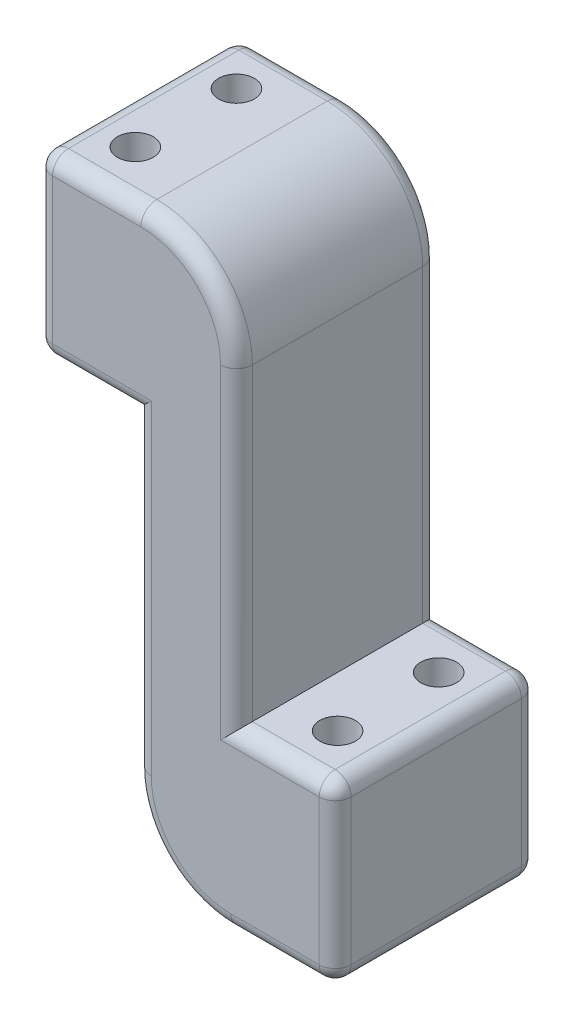
SolidWorks part; units mm, degrees
ref_plane "Front Plane" through (0, 0, 0) normal (0, 0, 1) x (1, 0, 0)
ref_plane "Top Plane" through (0, 0, 0) normal (0, 1, 0) x (1, 0, 0)
ref_plane "Right Plane" through (0, 0, 0) normal (1, 0, 0) x (0, 0, -1)
sketch "Sketch1" plane through (0, 0, 0) normal (0, 0, 1) x (1, 0, 0)
  line L0 (0, -23.8252) -> (-45.3315, -23.8252) construction
  line L1 (-2, 0) -> (-12.3952, 0)
  line L2 (0, -2) -> (0, -20.2504)
  line L3 (-2, -22.2504) -> (-12.3952, -22.2504)
  line L4 (-12.3952, 0) -> (-12.3952, -22.2504)
  line L5 (-25.0952, 28.5496) -> (-35.4904, 28.5496)
  line L6 (-25.0952, 28.5496) -> (-25.0952, 50.8)
  line L7 (-25.0952, 50.8) -> (-35.4904, 50.8)
  line L8 (-37.4904, 30.5496) -> (-37.4904, 48.8)
  line L9 (-25.0952, 50.8) -> (-24.3952, 50.8)
  line L10 (-12.3952, 38.8) -> (-12.3952, 0)
  line L11 (-12.3952, -22.2504) -> (-13.0952, -22.2504)
  line L12 (-25.0952, -10.2504) -> (-25.0952, 28.5496)
  line L13 (-48.1495, 26.9748) -> (9.176, 26.9748) construction
  arc A0 (-13.0952, -22.2504) -> (-25.0952, -10.2504) centre (-13.0952, -10.2504) cw
  arc A1 (-12.3952, 38.8) -> (-24.3952, 50.8) centre (-24.3952, 38.8) ccw
  arc A2 (0, -2) -> (-2, 0) centre (-2, -2) ccw
  arc A3 (0, -20.2504) -> (-2, -22.2504) centre (-2, -20.2504) cw
  arc A4 (-35.4904, 28.5496) -> (-37.4904, 30.5496) centre (-35.4904, 30.5496) cw
  arc A5 (-37.4904, 48.8) -> (-35.4904, 50.8) centre (-35.4904, 48.8) cw
  point P19 (0, 0)
  point P22 (0, -22.2504)
  point P29 (-30.2928, 28.5496)
  dimension "D6" = 12
  dimension "D7" = 2
  dimension "D1" = 22.2504
  dimension "D2" = 12.3952
  dimension "D3" = 12.7
  dimension "D4" = 1.5748
  dimension "D5" = 1.5748
  dimension "D8" = 50.8
extrude "Boss-Extrude1" add sketch "Sketch1" along normal blind 25.4 contours L10 A1 L9 L6 L12 A0 L11 L4 | A5 L8 A4 L5 L6 L7 | A3 L2 A2 L1 L4 L3
sketch "Sketch2" plane through (0, 50.8, 0) normal (0, 1, 0) x (1, 0, 0)
  line L0 (-35.4904, 0) -> (-24.3952, 0) construction
  line L1 (-37.4904, -25.4) -> (-37.4904, 0) construction
  line L2 (-35.4904, -25.4) -> (-24.3952, -25.4) construction
  line L3 (0, -25.4) -> (0, 0) construction
  circle A0 centre (-31.4452, -6.35) radius 2.25
  circle A1 centre (-31.4452, -19.05) radius 2.25
  circle A2 centre (-6.0452, -6.35) radius 2.25
  circle A3 centre (-6.0452, -19.05) radius 2.25
  dimension "D1" = 4.5
  dimension "D2" = 6.35
  dimension "D4" = 6.0452
  dimension "D5" = 6.35
  dimension "D6" = 6.0452
extrude "Cut-Extrude1" cut sketch "Sketch2" against normal through all
fillet "Fillet1" radius 2 28 edges at (-7.1976, 0, 0) (-0.5858, -0.5858, 0) (0, -11.1252, 0) (-0.5858, -21.6646, 0) (-7.5476, -22.2504, 0) (-21.5805, -18.7357, 0) (-7.1976, 0, 25.4) (-0.5858, -0.5858, 25.4) (0, -11.1252, 25.4) (-0.5858, -21.6646, 25.4) (-7.5476, -22.2504, 25.4) (-21.5805, -18.7357, 25.4) (-30.2928, 28.5496, 0) (-36.9046, 29.1354, 0) (-12.3952, 19.4, 0) (-15.9099, 47.2853, 0) (-29.9428, 50.8, 0) (-36.9046, 50.2142, 0) (-12.3952, 19.4, 25.4) (-30.2928, 28.5496, 25.4) (-36.9046, 29.1354, 25.4) (-37.4904, 39.6748, 0) (-37.4904, 39.6748, 25.4) (-36.9046, 50.2142, 25.4) (-29.9428, 50.8, 25.4) (-25.0952, 9.1496, 0) (-25.0952, 9.1496, 25.4) (-15.9099, 47.2853, 25.4)
